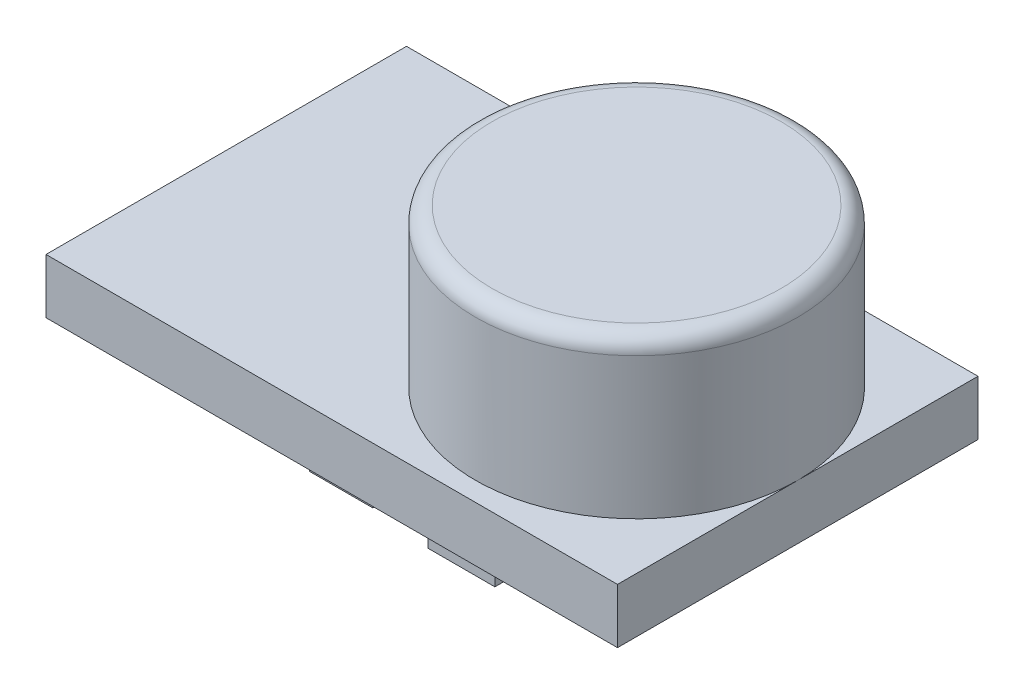
SolidWorks part; units mm, degrees
ref_plane "Front Plane" through (0, 0, 0) normal (0, 0, 1) x (1, 0, 0)
ref_plane "Top Plane" through (0, 0, 0) normal (0, 1, 0) x (1, 0, 0)
ref_plane "Right Plane" through (0, 0, 0) normal (1, 0, 0) x (0, 0, -1)
sketch "Sketch1" plane through (0, 0, 0) normal (0, 1, 0) x (1, 0, 0)
  line L1 (-8.6, 5.425) -> (8.6, 5.425)
  line L2 (-8.6, 5.425) -> (-8.6, -5.425)
  line L3 (-8.6, -5.425) -> (8.6, -5.425)
  line L4 (8.6, 5.425) -> (8.6, -5.425)
  line L5 (-8.6, 5.425) -> (8.6, -5.425) construction
  line L6 (-8.6, -5.425) -> (8.6, 5.425) construction
  point P0 (0, 0)
  dimension "D1" = 17.2
  dimension "D2" = 10.85
extrude "Boss-Extrude1" add sketch "Sketch1" along normal blind 1.65
sketch "Sketch2" plane through (0, 1.65, 0) normal (0, 1, 0) x (1, 0, 0)
  line L0 (-8.6, 0) -> (8.6, 0) construction
  line L1 (-8.6, 5.425) -> (-8.6, -5.425) construction
  line L2 (8.6, -5.425) -> (8.6, 5.425) construction
  circle A0 centre (3.75, 0) radius 4.85
  dimension "D1" = 9.7
extrude "Boss-Extrude2" add sketch "Sketch2" along normal blind 4.75
fillet "Fillet1" radius 0.5 1 edges at (3.75, 6.4, 4.85)
sketch "Sketch3" plane through (0, 0, 0) normal (0, -1, 0) x (1, 0, 0)
  line L1 (0, 1.3227) -> (-1.3595, 1.3227)
  line L2 (0, 1.3227) -> (0, -1.7085)
  line L3 (0, -1.7085) -> (-1.3595, -1.7085)
  line L4 (-1.3595, 1.3227) -> (-1.3595, -1.7085)
  line L5 (-1.5248, -2.2781) -> (0.2756, -2.2781)
  line L6 (-1.5248, -2.2781) -> (-1.5248, -3.2334)
  line L7 (-1.5248, -3.2334) -> (0.2756, -3.2334)
  line L8 (0.2756, -2.2781) -> (0.2756, -3.2334)
  line L9 (-3.9866, 0.9186) -> (-3.1231, 0.9186)
  line L10 (-3.9866, 0.9186) -> (-3.9866, -0.8083)
  line L11 (-3.9866, -0.8083) -> (-3.1231, -0.8083)
  line L12 (-3.1231, 0.9186) -> (-3.1231, -0.8083)
  line L13 (-5.4563, 0.9186) -> (-4.5378, 0.9186)
  line L14 (-5.4563, 0.9186) -> (-5.4563, -0.8083)
  line L15 (-5.4563, -0.8083) -> (-4.5378, -0.8083)
  line L16 (-4.5378, 0.9186) -> (-4.5378, -0.8083)
  line L17 (-1.6351, 4.4643) -> (0.2756, 4.4643)
  line L18 (-1.6351, 4.4643) -> (-1.6351, 3.5273)
  line L19 (-1.6351, 3.5273) -> (0.2756, 3.5273)
  line L20 (0.2756, 4.4643) -> (0.2756, 3.5273)
  line L21 (-1.6351, 3.2334) -> (0.2756, 3.2334)
  line L22 (-1.6351, 3.2334) -> (-1.6351, 2.2597)
  line L23 (-1.6351, 2.2597) -> (0.2756, 2.2597)
  line L24 (0.2756, 3.2334) -> (0.2756, 2.2597)
  line L25 (2.1495, 4.6847) -> (4.1703, 4.6847)
  line L26 (2.1495, 4.6847) -> (2.1495, 3.711)
  line L27 (2.1495, 3.711) -> (4.1703, 3.711)
  line L28 (4.1703, 4.6847) -> (4.1703, 3.711)
  line L29 (1.6351, 2.5169) -> (2.572, 2.5169)
  line L30 (1.6351, 2.5169) -> (1.6351, 0.4042)
  line L31 (1.6351, 0.4042) -> (2.572, 0.4042)
  line L32 (2.572, 2.5169) -> (2.572, 0.4042)
  line L33 (2.9394, 2.5169) -> (3.858, 2.5169)
  line L34 (2.9394, 2.5169) -> (2.9394, 0.4042)
  line L35 (2.9394, 0.4042) -> (3.858, 0.4042)
  line L36 (3.858, 2.5169) -> (3.858, 0.4042)
  line L37 (2.1495, -0.9186) -> (4.005, -0.9186)
  line L38 (2.1495, -0.9186) -> (2.1495, -1.9106)
  line L39 (2.1495, -1.9106) -> (4.005, -1.9106)
  line L40 (4.005, -0.9186) -> (4.005, -1.9106)
extrude "Boss-Extrude3" add sketch "Sketch3" along normal blind 1
